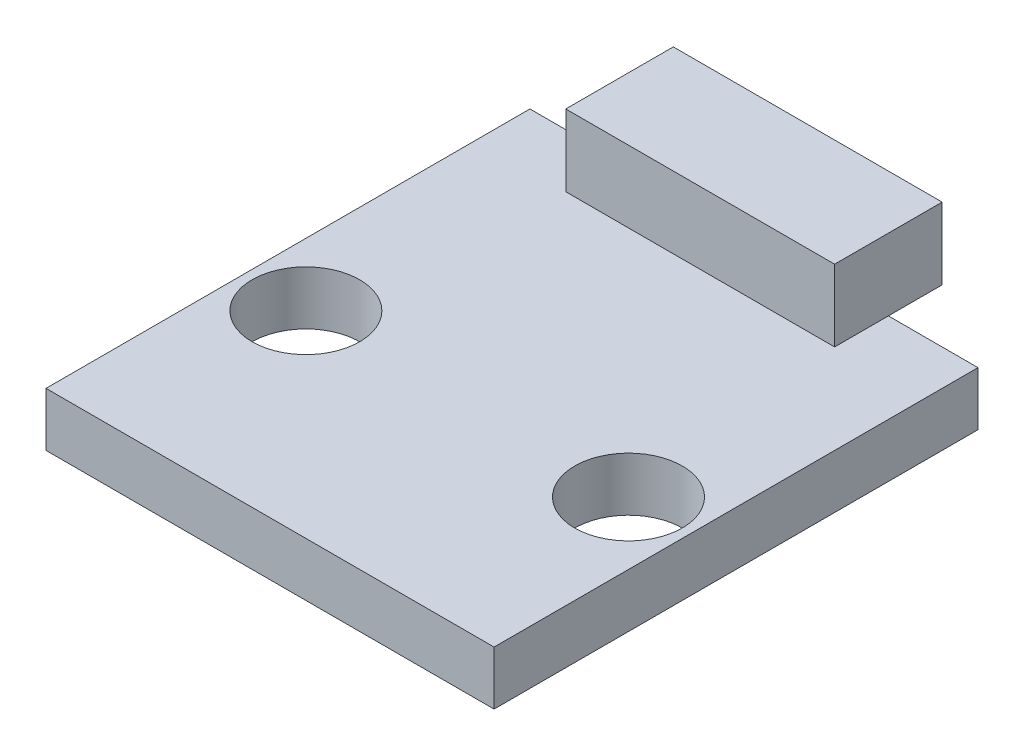
SolidWorks part; units mm, degrees
ref_plane "Front Plane" through (0, 0, 0) normal (0, 0, 1) x (1, 0, 0)
ref_plane "Top Plane" through (0, 0, 0) normal (0, 1, 0) x (1, 0, 0)
ref_plane "Right Plane" through (0, 0, 0) normal (1, 0, 0) x (0, 0, -1)
sketch "Sketch1" plane through (0, 0, 0) normal (0, 1, 0) x (1, 0, 0)
  line L1 (-6.25, -6.75) -> (6.25, -6.75)
  line L2 (-6.25, -6.75) -> (-6.25, 6.75)
  line L3 (-6.25, 6.75) -> (6.25, 6.75)
  line L4 (6.25, -6.75) -> (6.25, 6.75)
  line L5 (-6.25, -6.75) -> (6.25, 6.75) construction
  line L6 (-6.25, 6.75) -> (6.25, -6.75) construction
  point P0 (0, 0)
  dimension "D1" = 12.5
  dimension "D2" = 13.5
extrude "Boss-Extrude1" add sketch "Sketch1" along normal blind 1.5 contours L3 L4 L1 L2
sketch "Sketch2" plane through (0, 1.5, 0) normal (0, 1, 0) x (1, 0, 0)
  line L0 (-6.25, 6.75) -> (6.25, 6.75) construction
  line L1 (-3.75, 5.25) -> (3.75, 5.25)
  line L2 (-3.75, 5.25) -> (-3.75, 8.25)
  line L3 (-3.75, 8.25) -> (3.75, 8.25)
  line L4 (3.75, 5.25) -> (3.75, 8.25)
  line L5 (-3.75, 5.25) -> (3.75, 8.25) construction
  line L6 (-3.75, 8.25) -> (3.75, 5.25) construction
  point P0 (0, 6.75)
  dimension "D1" = 1.5
  dimension "D2" = 7.5
extrude "Boss-Extrude2" add sketch "Sketch2" along normal blind 2
sketch "Sketch3" plane through (0, 1.5, 0) normal (0, 1, 0) x (1, 0, 0)
  line L0 (-6.25, -6.75) -> (6.25, -6.75) construction
  line L3 (-6.25, -6.75) -> (-6.25, 6.75) construction
  line L4 (6.25, -6.75) -> (6.25, 6.75) construction
  circle A0 centre (-4.5, -1.25) radius 1.5
  circle A1 centre (4.5, -1.25) radius 1.5
  dimension "D2" = 3
  dimension "D1" = 5.5
  dimension "D3" = 1.75
  dimension "D4" = 1.75
extrude "Cut-Extrude4" cut sketch "Sketch3" against normal through all
equation "\"D4@Sketch3\"=\"D3@Sketch3\""
